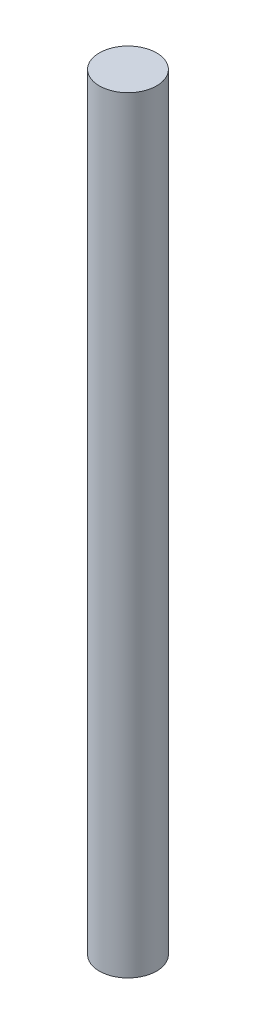
SolidWorks part; units mm, degrees
ref_plane "Front Plane" through (0, 0, 0) normal (0, 0, 1) x (1, 0, 0)
ref_plane "Top Plane" through (0, 0, 0) normal (0, 1, 0) x (1, 0, 0)
ref_plane "Right Plane" through (0, 0, 0) normal (1, 0, 0) x (0, 0, -1)
sketch "Sketch1" plane through (0, 0, 0) normal (0, 1, 0) x (1, 0, 0)
  circle A0 centre (0, 0) radius 1.905
  dimension "D1" = 3.81
extrude "Boss-Extrude1" add sketch "Sketch1" along normal blind 51.054
